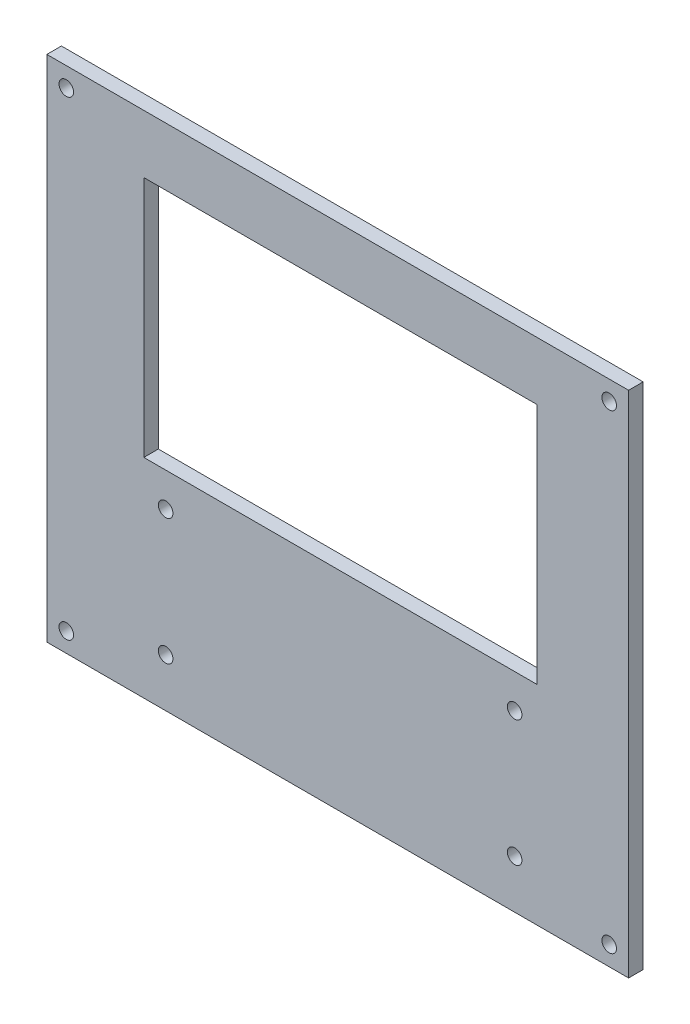
SolidWorks part; units mm, degrees
ref_plane "前视基准面" through (0, 0, 0) normal (0, 0, 1) x (1, 0, 0)
ref_plane "上视基准面" through (0, 0, 0) normal (0, 1, 0) x (1, 0, 0)
ref_plane "右视基准面" through (0, 0, 0) normal (1, 0, 0) x (0, 0, -1)
other "Configuration Table"
sketch "草图1" plane through (0, 0, 0) normal (0, 0, 1) x (1, 0, 0)
  line L1 (-60, 52.5) -> (60, 52.5)
  line L2 (-60, 52.5) -> (-60, -52.5)
  line L3 (-60, -52.5) -> (60, -52.5)
  line L4 (60, 52.5) -> (60, -52.5)
  line L5 (0, -52.5) -> (0, 52.5) construction
  line L6 (-60, 0) -> (60, 0) construction
  point P0 (0, 0)
  dimension "D1" = 120
  dimension "D2" = 105
extrude "凸台-拉伸1" add sketch "草图1" along normal blind 3
sketch "草图2" plane through (0, 0, 3) normal (0, 0, 1) x (1, 0, 0)
  line L0 (60, 52.5) -> (-60, 52.5) construction
  line L1 (-56, 48.5) -> (56, 48.5) construction
  line L2 (-56, 48.5) -> (-56, -48.5) construction
  line L3 (-56, -48.5) -> (56, -48.5) construction
  line L4 (56, 48.5) -> (56, -48.5) construction
  line L5 (0, -48.5) -> (0, 48.5) construction
  line L6 (-56, 0) -> (56, 0) construction
  line L7 (60, -52.5) -> (60, 52.5) construction
  circle A0 centre (-56, 48.5) radius 1.5
  circle A1 centre (56, 48.5) radius 1.5
  circle A2 centre (56, -48.5) radius 1.5
  circle A3 centre (-56, -48.5) radius 1.5
  point P0 (0, 0)
  dimension "D3" = 3
  dimension "D1" = 4
  dimension "D2" = 4
extrude "切除-拉伸1" cut sketch "草图2" against normal blind 10
sketch "草图3" plane through (0, 0, 0) normal (0, 0, -1) x (-1, 0, 0)
  line L1 (-41.1514, 40.5) -> (40, 40.5)
  line L2 (-41.1514, 40.5) -> (-41.1514, -9.5)
  line L3 (-41.1514, -9.5) -> (40, -9.5)
  line L4 (40, 40.5) -> (40, -9.5)
  line L5 (60, 52.5) -> (60, -52.5) construction
  line L6 (-60, 52.5) -> (60, 52.5) construction
  line L7 (60, -52.5) -> (-60, -52.5) construction
  line L8 (-60, -52.5) -> (-60, 52.5) construction
  circle A0 centre (-36.5, -42.5) radius 1.5
  circle A1 centre (35.5, -42.5) radius 1.5
  circle A2 centre (-36.5, -16.5) radius 1.5
  circle A3 centre (35.5, -16.5) radius 1.5
  point P18 (0, 0)
  dimension "D6" = 3
  dimension "D9" = 3
  dimension "D10" = 3
  dimension "D13" = 3
  dimension "D1" = 12
  dimension "D2" = 20
  dimension "D3" = 50
  dimension "D4" = 10
  dimension "D5" = 23.5
  dimension "D7" = 72
  dimension "D8" = 10
  dimension "D11" = 26
  dimension "D12" = 26
extrude "切除-拉伸2" cut sketch "草图3" against normal blind 10
